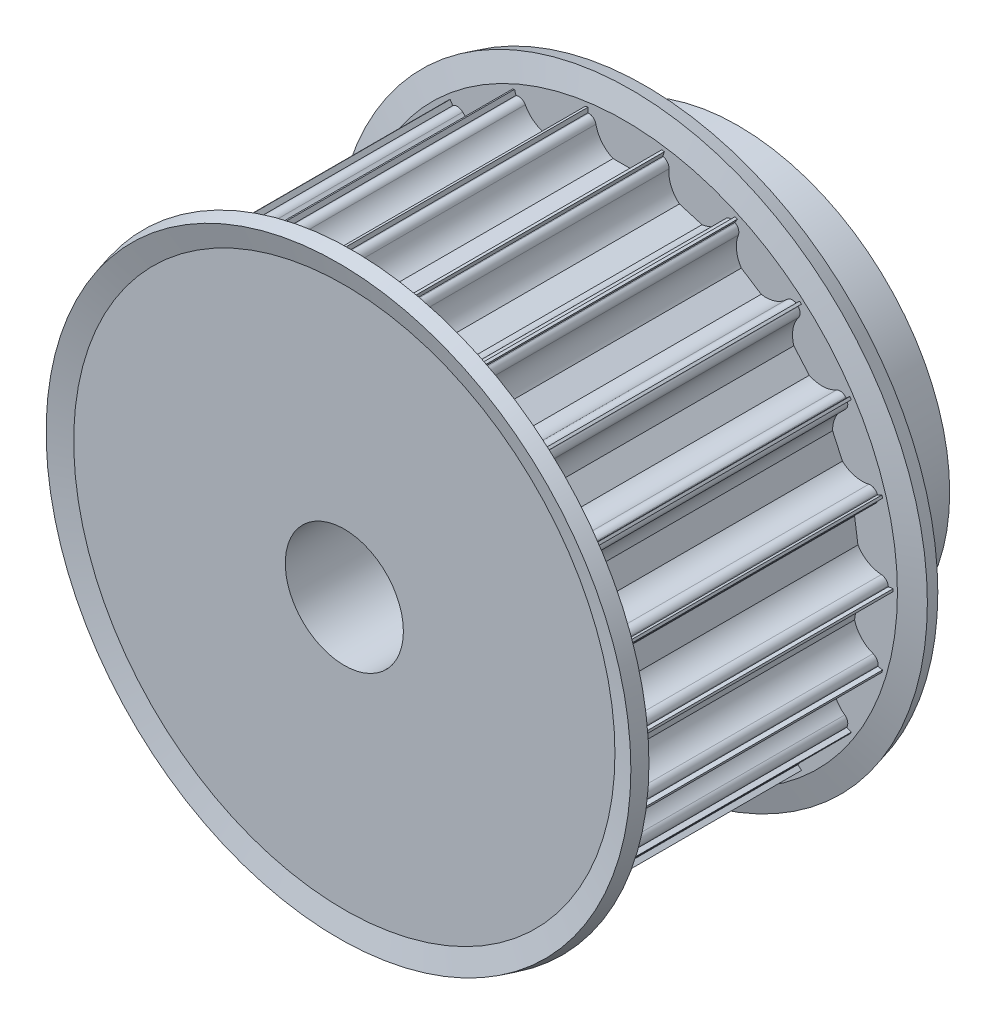
SolidWorks part; units mm, degrees
ref_plane "Front Plane" through (0, 0, 0) normal (0, 0, 1) x (1, 0, 0)
ref_plane "Top Plane" through (0, 0, 0) normal (0, 1, 0) x (1, 0, 0)
ref_plane "Right Plane" through (0, 0, 0) normal (1, 0, 0) x (0, 0, -1)
sketch "Sketch1" plane through (0, 0, 0) normal (1, 0, 0) x (0, 0, -1)
  line L0 (0, 6) -> (0, 27.25)
  line L1 (0, 27.25) -> (30, 27.25)
  line L2 (30, 27.25) -> (30, 21.5)
  line L3 (30, 21.5) -> (40, 21.5)
  line L4 (40, 21.5) -> (40, 6)
  line L5 (40, 6) -> (0, 6)
  line L6 (-29.5361, 0) -> (53.0718, 0) construction
  dimension "D1" = 21.25
  dimension "D2" = 30
  dimension "D3" = 82.6079
  dimension "D4" = 10
  dimension "D5" = 15.5
  dimension "D6" = 40
  dimension "D7" = 6
revolve "Revolve1" add sketch "Sketch1" angle 360 about L6
sketch "Sketch2" plane through (0, 0, 0) normal (0, 0, 1) x (1, 0, 0)
  line L0 (3.6742, 26.5) -> (3.75, 26.5)
  line L1 (-3.75, 28.5) -> (3.75, 28.5)
  line L2 (-3.75, 28.5) -> (-3.75, 26.5)
  line L3 (-3.75, 26.5) -> (-3.6742, 26.5)
  line L4 (3.75, 28.5) -> (3.75, 26.5)
  line L5 (-1.199, 23.75) -> (1.199, 23.75)
  arc A0 (-2.9394, 25.9) -> (-1.199, 23.75) centre (0, 26.5) ccw
  arc A1 (-2.9394, 25.9) -> (-3.6742, 26.5) centre (-3.6742, 25.75) ccw
  arc A2 (2.9394, 25.9) -> (3.6742, 26.5) centre (3.6742, 25.75) cw
  arc A3 (1.199, 23.75) -> (2.9394, 25.9) centre (0, 26.5) ccw
  point P14 (0, 0)
  dimension "D1" = 3
  dimension "D5" = 0.75
  dimension "D6" = 0.75
  dimension "D2" = 2
  dimension "D3" = 7.5
  dimension "D4" = 26.5
  dimension "D7" = 2.75
extrude "Cut-Extrude1" cut sketch "Sketch2" against normal through all
sketch "Sketch3" plane through (0, 0, 0) normal (1, 0, 0) x (0, 0, -1)
  line L0 (-21.2099, 0) -> (61.6638, 0) construction
  dimension "D1" = 82.8737
pattern_circular "CirPattern1" count 22 over 360 about axis through (0, 0, 0) along (0, 0, 1) of "Cut-Extrude1"
sketch "Sketch4" plane through (0, 0, 0) normal (1, 0, 0) x (0, 0, -1)
  line L0 (1.5, 27.6907) -> (0.0511, 27.3025) construction
  line L1 (0, 27.6907) -> (1.5, 27.6907) construction
  line L2 (0, 27.6907) -> (0, 22.6907)
  line L3 (0, 22.6907) -> (1.5, 22.6907)
  line L4 (1.5, 27.6907) -> (1.5, 22.6907)
  line L5 (1.5, 27.6907) -> (0.8569, 30.0907)
  line L6 (0.0511, 27.3025) -> (-0.592, 29.7025)
  line L7 (0.8569, 30.0907) -> (-0.592, 29.7025)
  line L8 (30, 26.9907) -> (0, 26.9907) construction
  line L9 (15, 37.195) -> (15, -35.9286) construction
  line L10 (0, 25.679) -> (0, 23.1257) construction
  line L11 (30, 27.6907) -> (28.5, 27.6907) construction
  line L12 (28.5, 27.6907) -> (29.9489, 27.3025) construction
  line L13 (29.1431, 30.0907) -> (30.592, 29.7025)
  line L14 (29.9489, 27.3025) -> (30.592, 29.7025)
  line L15 (28.5, 27.6907) -> (29.1431, 30.0907)
  line L16 (28.5, 27.6907) -> (28.5, 22.6907)
  line L17 (30, 22.6907) -> (28.5, 22.6907)
  line L18 (30, 27.6907) -> (30, 22.6907)
  dimension "D1" = 165
  dimension "D2" = 5
  dimension "D3" = 1.5
  dimension "D4" = 2.4
  dimension "D5" = 1.5
  dimension "D6" = 0.7
  dimension "D7" = 73.1236
  dimension "D8" = 0
revolve "Revolve2" add sketch "Sketch4" angle 360 about L0
